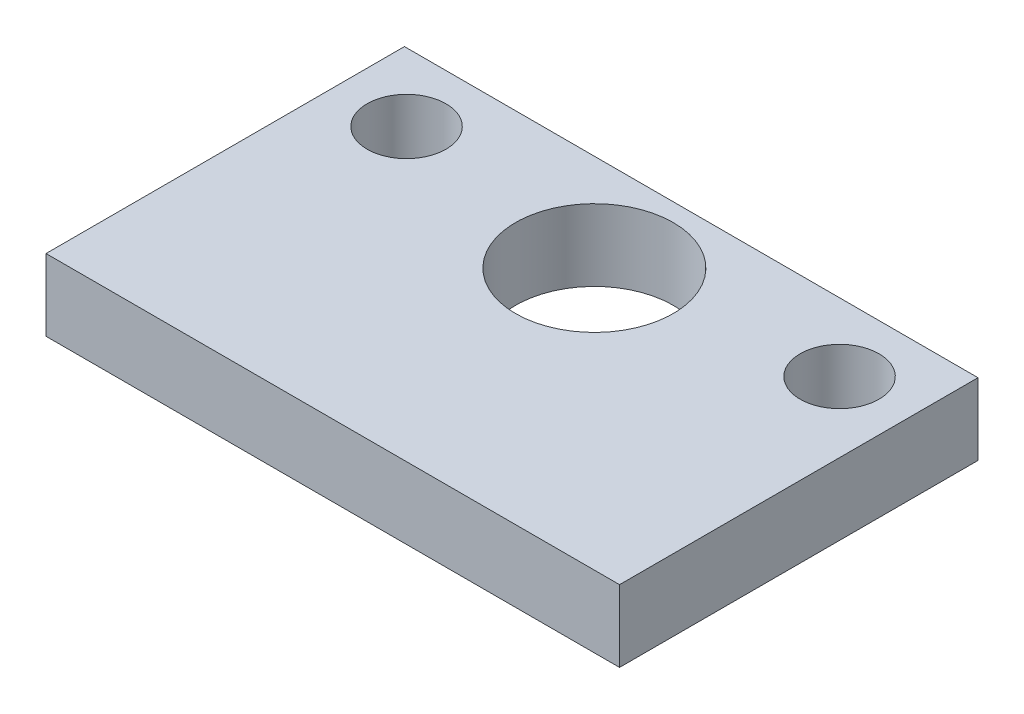
SolidWorks part; units mm, degrees
ref_plane "Front Plane" through (0, 0, 0) normal (0, 0, 1) x (1, 0, 0)
ref_plane "Top Plane" through (0, 0, 0) normal (0, 1, 0) x (1, 0, 0)
ref_plane "Right Plane" through (0, 0, 0) normal (1, 0, 0) x (0, 0, -1)
sketch "Sketch1" plane through (0, 0, 0) normal (0, 1, 0) x (1, 0, 0)
  line L1 (-35, -25) -> (45, -25)
  line L2 (-35, -25) -> (-35, 25)
  line L3 (-35, 25) -> (45, 25)
  line L4 (45, -25) -> (45, 25)
  point P0 (0, 0)
  dimension "D1" = 50
  dimension "D2" = 80
extrude "Boss-Extrude1" add sketch "Sketch1" along normal blind 10
sketch "Sketch2" plane through (0, 10, 0) normal (0, 1, 0) x (1, 0, 0)
  line L0 (-35, 25) -> (-35, -25) construction
  line L1 (45, -25) -> (45, 25) construction
  line L2 (5, 25) -> (5, 11.4913) construction
  line L3 (45, 25) -> (-35, 25) construction
  circle A0 centre (-25.2003, 15.4913) radius 5.5
  circle A1 centre (35.2, 15.4913) radius 5.5
  circle A2 centre (5, 11.4913) radius 11
  dimension "D1" = 11
  dimension "D2" = 9.7997
  dimension "D3" = 9.8
  dimension "D4" = 0
extrude "Cut-Extrude1" cut sketch "Sketch2" against normal through all
sketch "Sketch3" plane through (0, 0, 0) normal (0, -1, 0) x (1, 0, 0)
  line L0 (5, 25) -> (5, 13) construction
  line L2 (-35, 25) -> (45, 25) construction
  circle A0 centre (5, 13) radius 10
  dimension "D1" = 20
extrude "Cut-Extrude2" cut sketch "Sketch3" against normal blind 5
